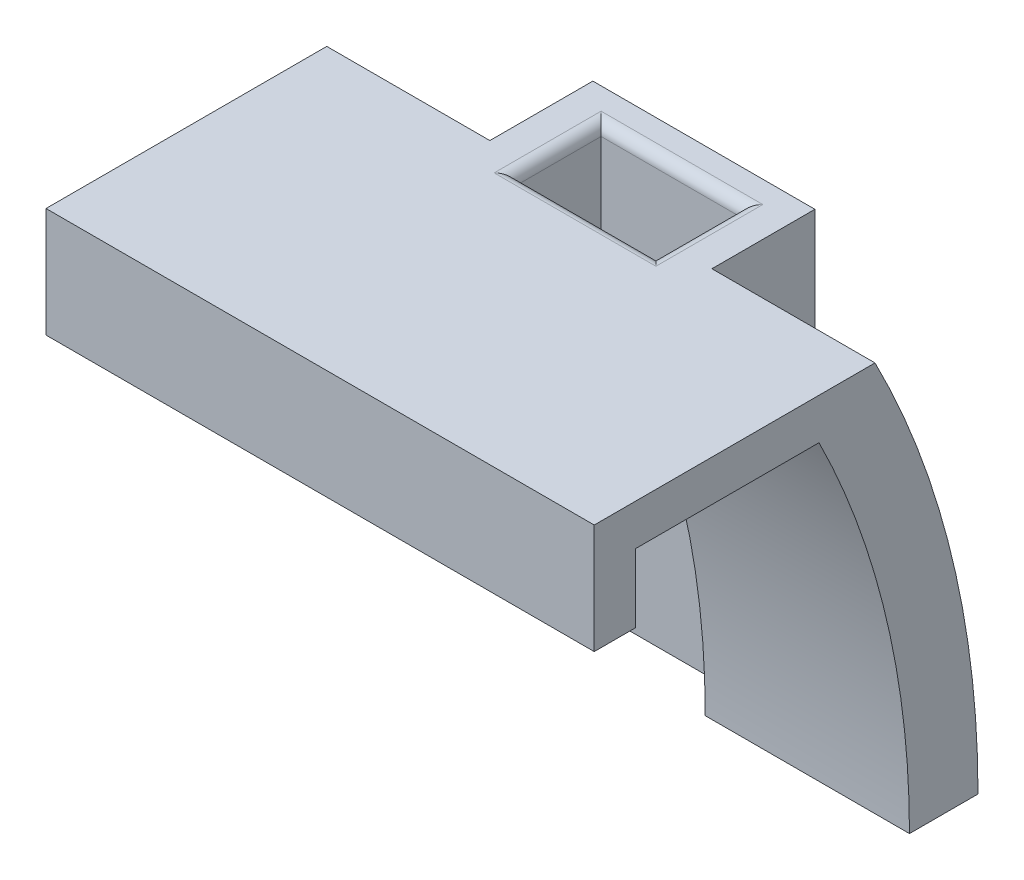
SolidWorks part; units mm, degrees
ref_plane "Front Plane" through (0, 0, 0) normal (0, 0, 1) x (1, 0, 0)
ref_plane "Top Plane" through (0, 0, 0) normal (0, 1, 0) x (1, 0, 0)
ref_plane "Right Plane" through (0, 0, 0) normal (1, 0, 0) x (0, 0, -1)
sketch "Sketch2" plane through (0, 0, 0) normal (1, 0, 0) x (0, 0, -1)
  line L1 (25.4, -35.56) -> (0, -35.56) construction
  line L6 (0, 0) -> (0, -6.35)
  line L7 (0, -6.35) -> (-3.81, -6.35)
  line L8 (-3.81, -6.35) -> (-3.81, 3.81)
  line L9 (-3.81, 3.81) -> (22.2056, 3.81)
  line L10 (25.4, -35.56) -> (31.75, -35.56)
  line L11 (0, 0) -> (17.018, 0)
  arc A0 (25.4, -35.56) -> (17.018, 0) centre (-54.2213, -35.56) ccw
  arc A1 (31.75, -35.56) -> (22.2056, 3.81) centre (-54.2213, -35.56) ccw
  arc A2 (31.75, -35.56) -> (22.6995, 2.836) centre (-54.2213, -35.56) ccw construction
  dimension "D1" = 17.018
  dimension "D2" = 35.56
  dimension "D3" = 8.382
  dimension "D4" = 3.81
  dimension "D5" = 6.35
  dimension "D6" = 6.35
  dimension "D7" = 10.16
extrude "Boss-Extrude1" add sketch "Sketch2" along normal mid plane 50.8
sketch "Sketch3" plane through (0, 0, 0) normal (1, 0, 0) x (0, 0, -1)
  line L0 (31.75, -35.56) -> (31.75, 3.81)
  line L1 (22.2056, 3.81) -> (31.75, 3.81)
  line L2 (22.2056, 3.81) -> (31.75, -35.56)
extrude "Boss-Extrude2" add sketch "Sketch3" along normal mid plane 20.574
ref_plane "Plane1" through (0, 3.81, 0) normal (0, 1, 0) x (1, 0, 0)
sketch "Sketch4" plane through (0, 3.81, 0) normal (0, 1, 0) x (1, 0, 0)
  line L1 (-6.477, 28.702) -> (6.477, 28.702)
  line L2 (-6.477, 28.702) -> (-6.477, 20.828)
  line L3 (-6.477, 20.828) -> (6.477, 20.828)
  line L4 (6.477, 28.702) -> (6.477, 20.828)
  dimension "D1" = 7.874
  dimension "D2" = 12.954
  dimension "D3" = 6.477
  dimension "D4" = 3.048
extrude "Cut-Extrude1" cut sketch "Sketch4" against normal through all
fillet "Fillet2" radius 1.016 4 edges at (6.477, 3.81, -24.765) (0, 3.81, -20.828) (-6.477, 3.81, -24.765) (0, 3.81, -28.702)
